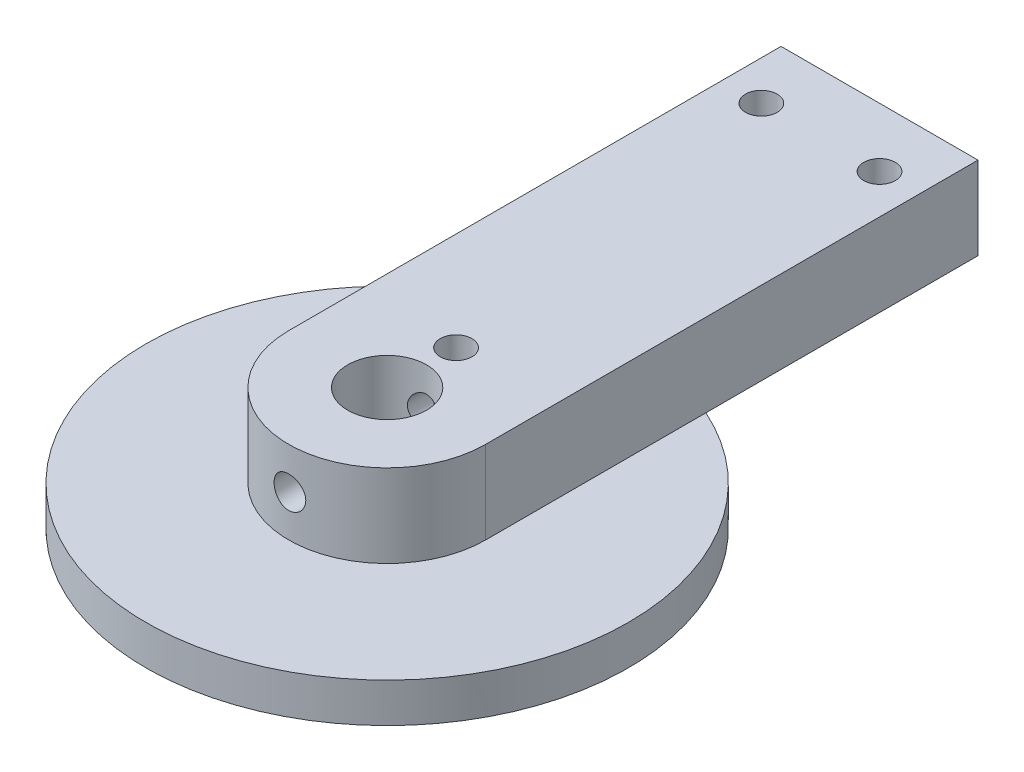
SolidWorks part; units mm, degrees
material "6061 Alloy"
ref_plane "Front Plane" through (0, 0, 0) normal (0, 0, 1) x (1, 0, 0)
ref_plane "Top Plane" through (0, 0, 0) normal (0, 1, 0) x (1, 0, 0)
ref_plane "Right Plane" through (0, 0, 0) normal (1, 0, 0) x (0, 0, -1)
sketch "Sketch1" plane through (0, 0, 0) normal (0, 1, 0) x (1, 0, 0)
  line L0 (-15.875, 0) -> (-15.875, 79.375)
  line L1 (-15.875, 79.375) -> (15.875, 79.375)
  line L2 (15.875, 79.375) -> (15.875, 0)
  arc A0 (-15.875, 0) -> (15.875, 0) centre (0, 0) ccw
  point P14 (0, -15.875)
  dimension "D1" = 95.25
  dimension "D3" = 31.75
extrude "Boss-Extrude1" add sketch "Sketch1" along normal blind 13.3524
sketch "Sketch4" plane through (0, 0, 0) normal (0, -1, 0) x (1, 0, 0)
  circle A0 centre (0, 0) radius 38.8938
  dimension "D1" = 77.7875
extrude "Boss-Extrude2" add sketch "Sketch4" along normal blind 4.7625
sketch "Sketch11" plane through (0, 0, 0) normal (0, 1, 0) x (1, 0, 0)
  line L1 (-10.6938, -10.0099) -> (33.8661, -10.0099)
  line L2 (-10.6938, -10.0099) -> (-10.6938, -2.4242)
  line L3 (-10.6938, -2.4242) -> (33.8661, -2.4242)
  line L4 (33.8661, -10.0099) -> (33.8661, -2.4242)
  dimension "D1" = 7.5856
extrude "Boss-Extrude5" [suppressed] add sketch "Sketch11" along normal blind 20.828
sketch "Sketch2" plane through (0, 13.3524, 0) normal (0, 1, 0) x (1, 0, 0)
  circle A0 centre (0, 0) radius 6.35
extrude "Cut-Extrude1" cut sketch "Sketch2" against normal through all both and the other way through all
sketch "Sketch5" plane through (0, -4.7625, 0) normal (0, -1, 0) x (1, 0, 0)
  circle A0 centre (0, 0) radius 38.8938
  circle A1 centre (0, 0) radius 28.575
  dimension "D1" = 57.15
  dimension "D2" = 77.7875
extrude "Boss-Extrude3" add sketch "Sketch5" along normal blind 1.5875
sketch "Sketch6" plane through (0, 0, -79.375) normal (0, 0, -1) x (-1, 0, 0)
  line L0 (-15.875, 0) -> (15.875, 0) construction
  line L1 (0, 0) -> (32.2769, 0)
  line L2 (0, 0) -> (0, 19.5339)
  line L3 (0, 19.5339) -> (32.2769, 19.5339)
  line L4 (32.2769, 0) -> (32.2769, 19.5339)
extrude "Boss-Extrude4" [suppressed] add sketch "Sketch6" along normal blind 3.175
mirror "Mirror1" [suppressed] about plane through (0, 0, 0) normal (1, 0, 0)
sketch "Sketch9" [suppressed] plane through (0, 0, -15.7935) normal (0, 0, -1) x (-1, 0, 0)
  line L0 (-32.2769, 9.767) -> (32.2769, 9.767) construction
  line L1 (-32.2769, 0) -> (-32.2769, 19.5339) construction
  line L2 (32.2769, 0) -> (32.2769, 19.5339) construction
hole_wizard "1/4-28 Tapped Hole1" [suppressed] positions "Sketch7" profile "Sketch8" tap size "1/4-28" standard "ANSI Inch"
sketch "Sketch7" [suppressed] plane through (0, 0, -15.7935) normal (0, 0, -1) x (-1, 0, 0)
  line L1 (-23.8125, 9.767) -> (-32.2769, 9.767) construction
  line L3 (23.8125, 9.767) -> (32.2769, 9.767) construction
  line L5 (-23.8125, 9.767) -> (-23.8125, 11.037) construction
  line L6 (-23.8125, 11.037) -> (23.8125, 11.037) construction
  line L8 (23.8125, 11.037) -> (23.8125, 9.767) construction
  point P0 (-23.8125, 11.037)
  point P10 (23.8125, 11.037)
  dimension "D1" = 47.625
  dimension "D2" = 1.27
sketch "Sketch8" plane through (23.8125, 11.037, -15.7935) normal (1, 0, 0) x (0, 1, 0)
  line L0 (0, 0) -> (0, 3.175)
  line L1 (0, 3.175) -> (2.7051, 3.175)
  line L2 (2.7051, 3.175) -> (2.7051, 0)
  line L5 (2.7051, 0) -> (0, 0)
  line L11 (0, -6.35) -> (0, 107.95) construction
  dimension "Thru Tap Drill Dia." = 5.4102
  dimension "Thru Tap Drill Depth" = 3.175
cosmetic thread "Hole Thread2" [suppressed] parameters "D2"=6.35
cosmetic thread "Hole Thread6" [suppressed] parameters "D2"=6.35
mirror "Mirror2" [suppressed] about plane through (0, 0, 0) normal (1, 0, 0)
cosmetic thread "Hole Thread3" [suppressed] parameters "D2"=6.35
sketch "Sketch12" [suppressed] plane through (0, 0, 2.4242) normal (0, 0, -1) x (-1, 0, 0)
  circle A0 centre (-24.487, 13.2896) radius 6.35
extrude "Cut-Extrude2" [suppressed] cut sketch "Sketch12" against normal through all
hole_wizard "1/4-20 Tapped Hole1" positions "Sketch13" profile "Sketch15" tap size "1/4-20" standard "ANSI Inch" end condition through all
sketch "Sketch13" plane through (0, 0, -79.375) normal (0, 0, -1) x (-1, 0, 0)
  line L0 (-15.875, 6.6762) -> (15.875, 6.6762) construction
  line L1 (-15.875, 13.3524) -> (-15.875, 0) construction
  line L2 (15.875, 13.3524) -> (15.875, 0) construction
  line L4 (0, 0) -> (0, 13.3524) construction
  line L5 (-15.875, 13.3524) -> (15.875, 13.3524) construction
  point P0 (0, 6.6762)
sketch "Sketch15" plane through (0, 6.6762, -79.375) normal (1, 0, 0) x (0, 1, 0)
  line L0 (0, 0) -> (0, 118.2688)
  line L1 (0, 118.2688) -> (2.5527, 118.2688)
  line L2 (2.5527, 118.2688) -> (2.5527, 0)
  line L5 (2.5527, 0) -> (0, 0)
  line L11 (0, -6.35) -> (0, 107.95) construction
  dimension "Thru Tap Drill Dia." = 5.1054
  dimension "Thru Tap Drill Depth" = 118.2688
cosmetic thread "Hole Thread7" parameters "D2"=6.35
hole_wizard "1/4-20 Tapped Hole2" positions "Sketch20" profile "Sketch21" tap size "1/4-20" standard "ANSI Inch"
sketch "Sketch20" plane through (0, 13.3524, 0) normal (0, 1, 0) x (1, 0, 0)
  line L0 (0, 79.375) -> (0, 0) construction
  line L1 (15.875, 79.375) -> (-15.875, 79.375) construction
  point P0 (-9.525, 69.85)
  point P2 (9.525, 69.85)
  point P5 (0, 11.1125)
  point P32 (0, 0)
  point P33 (9.525, 69.85)
  point P34 (-9.525, 69.85)
  dimension "D2" = 68.2625
sketch "Sketch21" plane through (-9.525, 13.3524, -69.85) normal (1, 0, 0) x (0, 0, 1)
  line L0 (0, 0) -> (0, 119.8038)
  line L1 (0, 119.8038) -> (2.5527, 118.27)
  line L2 (2.5527, 118.27) -> (2.5527, 0)
  line L5 (2.5527, 0) -> (0, 0)
  line L10 (0, 119.8038) -> (-2.5527, 118.27) construction
  line L11 (0, -6.35) -> (0, 107.95) construction
  dimension "Tap Drill Dia." = 5.1054
  dimension "Tap Drill Depth" = 118.27
  dimension "Drill Angle" = 118
cosmetic thread "Hole Thread8" parameters "D1"=95.25, "D2"=6.35
cosmetic thread "Hole Thread9" parameters "D1"=95.25, "D2"=6.35
cosmetic thread "Hole Thread10" parameters "D1"=95.25, "D2"=6.35
